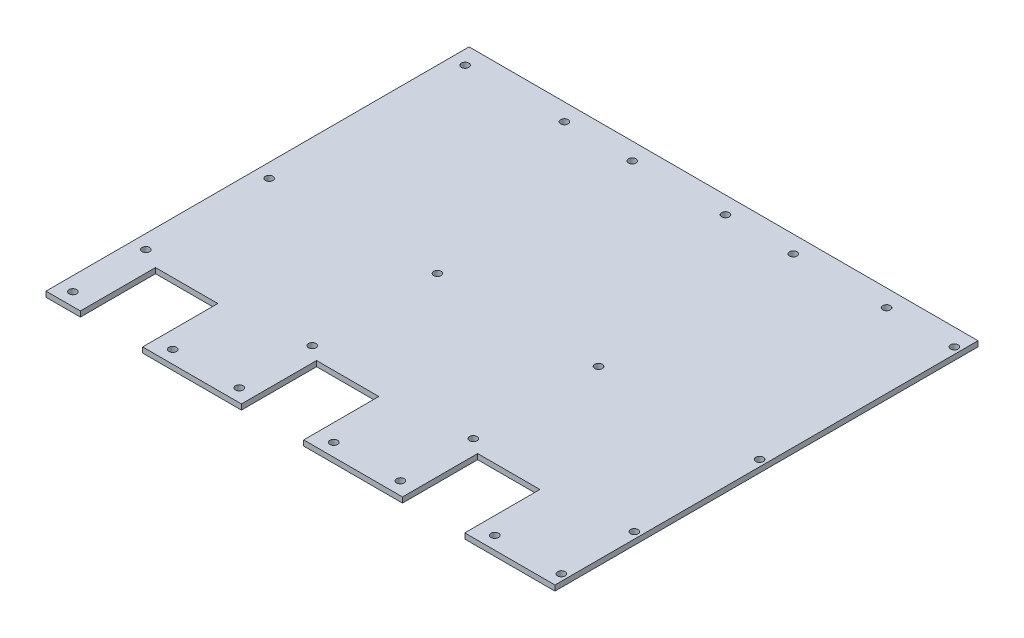
SolidWorks part; units mm, degrees
ref_plane "Płaszczyzna przednia" through (0, 0, 0) normal (0, 0, 1) x (1, 0, 0)
ref_plane "Płaszczyzna górna" through (0, 0, 0) normal (0, 1, 0) x (1, 0, 0)
ref_plane "Płaszczyzna prawa" through (0, 0, 0) normal (1, 0, 0) x (0, 0, -1)
sketch "Szkic1" plane through (0, 0, 0) normal (0, 1, 0) x (1, 0, 0)
  line L5 (0, 0) -> (237, 0)
  line L6 (0, 0) -> (0, 197)
  line L7 (0, 197) -> (237, 197)
  line L8 (237, 0) -> (237, 197)
  dimension "D1" = 197
  dimension "D2" = 237
extrude "Dodanie-wyciągnięcie1" add sketch "Szkic1" along normal blind 2.5 contours L6 L5 L8 L7
sketch "Szkic2" plane through (0, 2.5, 0) normal (0, 1, 0) x (1, 0, 0)
  line L42 (30.5, 0) -> (30.5, 22.6779) construction
  line L43 (0, 0) -> (237, 0) construction
  line L44 (0, 0) -> (0, 197) construction
  line L45 (45, 35) -> (16, 35)
  line L48 (77, 56) -> (13.9491, 56)
  line L49 (13.5, 53.9289) -> (13.5, 0)
  line L50 (13.5, 0) -> (15.5, 0)
  line L51 (15.5, 0) -> (15.5, 36)
  line L52 (15.5, 36) -> (45.5, 36)
  line L53 (45.5, 36) -> (45.5, 0)
  line L54 (45.5, 0) -> (47.5, 0)
  line L55 (47.5, 0) -> (47.5, 48)
  line L56 (47.5, 48) -> (59, 48)
  line L57 (59, 48) -> (59, 30.5)
  line L58 (59, 30.5) -> (77, 30.5)
  line L59 (77, 30.5) -> (77, 56)
  line L62 (45, 35) -> (45, 0)
  line L63 (45, 0) -> (16, 0)
  line L64 (16, 35) -> (16, 0)
  line L65 (45, 35) -> (16, 0) construction
  line L66 (45, 0) -> (16, 35) construction
  arc A4 (13.9491, 56) -> (13.5, 53.9289) centre (18.5, 53.9289) ccw
  point P23 (30.5, 17.5)
  dimension "D1" = 35
  dimension "D2" = 29
  dimension "D3" = 30.5
extrude "Wytnij-wyciągnięcie1" cut sketch "Szkic2" against normal blind 3 contours L62 L45 L64 L63
pattern_linear "Szyk liniowy1" count 3 spacing 75 along (1, 0, 0) of "Wytnij-wyciągnięcie1"
sketch "Szkic3" plane through (0, 2.5, 0) normal (0, 1, 0) x (1, 0, 0)
  line L0 (6.5, 19.2871) -> (84, 19.2871) construction
  line L1 (6.5, 33.818) -> (84, 33.818) construction
  circle A0 centre (159, 189) radius 2
  circle A1 centre (127.4112, 189) radius 2
  circle A2 centre (159, 98.2808) radius 2
  circle A3 centre (159, 6) radius 2
  circle A4 centre (128, 6) radius 2
  circle A5 centre (234, 189) radius 2
  circle A6 centre (202.4112, 189) radius 2
  circle A7 centre (234, 98.2808) radius 2
  circle A8 centre (84, 189) radius 2
  circle A9 centre (52.4112, 189) radius 2
  circle A10 centre (6.5, 188.67) radius 2
  circle A11 centre (84, 98.2808) radius 2
  circle A12 centre (84, 6) radius 2
  circle A13 centre (53, 6) radius 2
  circle A14 centre (6.5, 6) radius 2
  circle A15 centre (6.5, 97.4363) radius 2
  circle A16 centre (234, 6) radius 2
  circle A17 centre (203, 6) radius 2
  circle A22 centre (234, 40) radius 2
  circle A23 centre (159, 40) radius 2
  circle A24 centre (84, 40) radius 2
  circle A25 centre (6.5, 40) radius 2
  dimension "D1" = 3
sketch "Szkic6" plane through (0, 2.5, 0) normal (0, 1, 0) x (1, 0, 0)
  point P0 (6.5, 6)
  point P2 (53, 6)
  point P4 (84, 6)
  point P6 (84, 98.2808)
  point P8 (6.5, 97.4363)
  point P10 (6.5, 188.67)
  point P12 (52.4112, 189)
  point P14 (84, 189)
  point P16 (127.4112, 189)
  point P18 (128, 6)
  point P20 (159, 6)
  point P22 (203, 6)
  point P24 (234, 6)
  point P26 (159, 98.2808)
  point P28 (234, 98.2808)
  point P30 (234, 189)
  point P32 (202.4112, 189)
  point P34 (159, 189)
  point P37 (6.5, 40)
  point P39 (84, 40)
  point P41 (159, 40)
  point P43 (234, 40)
hole_wizard "Otwory ustalające Ø4.0mm1" positions "Szkic6" profile "Szkic5" hole size "Ø4.0" standard "DIN"
sketch "Szkic5" plane through (6.5, 2.5, -6) normal (1, 0, 0) x (0, 0, 1)
  line L0 (0, 0) -> (0, 10)
  line L1 (0, 10) -> (1.75, 10)
  line L2 (1.75, 10) -> (1.75, 0)
  line L5 (1.75, 0) -> (0, 0)
  line L10 (0, 10) -> (-1.75, 10) construction
  line L11 (0, -6.35) -> (0, 107.95) construction
  dimension "Średnica otworu" = 3.5
  dimension "Głębokość otworu" = 10
  dimension "Kąt wiertła" = 180
